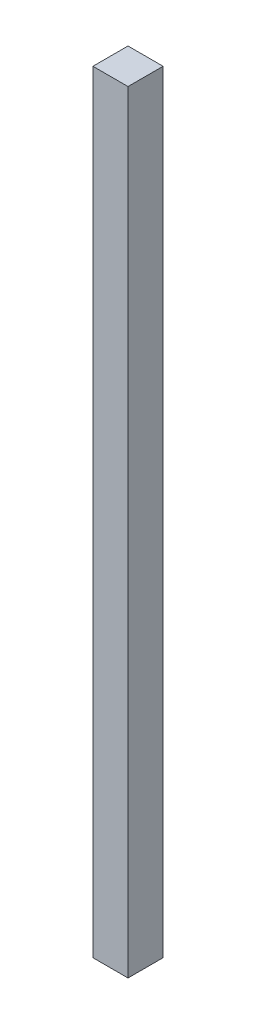
SolidWorks part; units mm, degrees
ref_plane "Front Plane" through (0, 0, 0) normal (0, 0, 1) x (1, 0, 0)
ref_plane "Top Plane" through (0, 0, 0) normal (0, 1, 0) x (1, 0, 0)
ref_plane "Right Plane" through (0, 0, 0) normal (1, 0, 0) x (0, 0, -1)
sketch "Sketch1" plane through (0, 0, 0) normal (0, 1, 0) x (1, 0, 0)
  line L1 (0, 0) -> (-25, 0)
  line L2 (0, 0) -> (0, -25)
  line L3 (0, -25) -> (-25, -25)
  line L4 (-25, 0) -> (-25, -25)
  dimension "D1" = 25
  dimension "D2" = 25
extrude "Boss-Extrude1" add sketch "Sketch1" along normal blind 550
